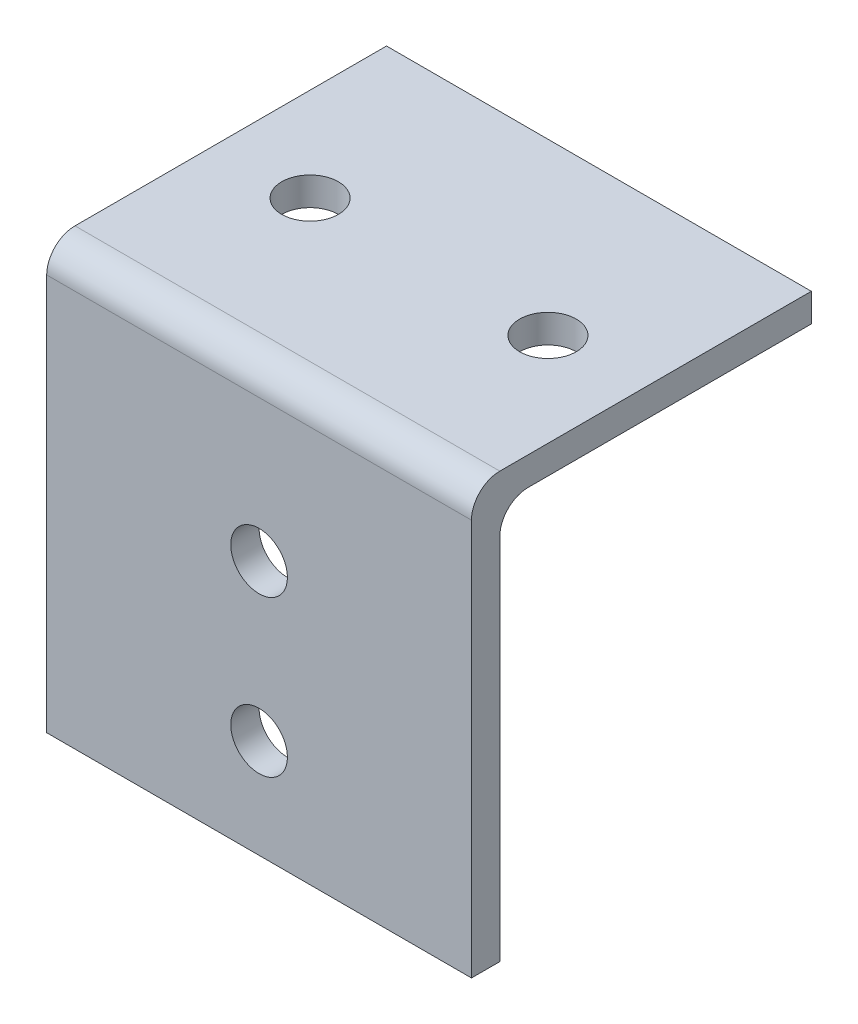
SolidWorks part; units mm, degrees
ref_plane "Front Plane" through (0, 0, 0) normal (0, 0, 1) x (1, 0, 0)
ref_plane "Top Plane" through (0, 0, 0) normal (0, 1, 0) x (1, 0, 0)
ref_plane "Right Plane" through (0, 0, 0) normal (1, 0, 0) x (0, 0, -1)
sketch "Sketch1" plane through (0, 0, 0) normal (0, 1, 0) x (1, 0, 0)
  line L0 (-19.5834, -8.6292) -> (18.5166, -8.6292) construction
  line L1 (-19.5834, 14.2308) -> (-5.08, 14.2308)
  line L2 (-19.5834, 14.2308) -> (-19.5834, -13.7092)
  line L3 (-19.5834, -13.7092) -> (18.5166, -13.7092)
  line L4 (18.5166, 14.2308) -> (18.5166, -13.7092)
  line L5 (-19.5834, -1.0092) -> (18.5166, -1.0092) construction
  line L6 (-5.08, 14.2308) -> (5.08, 14.2308)
  line L12 (5.08, 14.2308) -> (18.5166, 14.2308)
  circle A1 centre (-11.2014, -1.0092) radius 2.54
  circle A2 centre (10.1346, -1.0092) radius 2.54
  dimension "D1" = 22.86
  dimension "D4" = 5.08
  dimension "D5" = 5.08
  dimension "D2" = 38.1
  dimension "D3" = 27.94
  dimension "D6" = 8.382
  dimension "D7" = 8.382
  dimension "D9" = 15.24
extrude "Boss-Extrude1" add sketch "Sketch1" along normal blind 2.54
sketch "Sketch2" plane through (0, 0, 13.7092) normal (0, 0, 1) x (1, 0, 0)
  line L0 (18.5166, 2.54) -> (18.5166, 0) construction
  line L1 (-19.5834, 2.54) -> (18.5166, 2.54)
  line L2 (-19.5834, 2.54) -> (-19.5834, -35.56)
  line L3 (-19.5834, -35.56) -> (18.5166, -35.56)
  line L4 (18.5166, 2.54) -> (18.5166, -35.56)
  line L5 (-0.5334, 2.54) -> (-0.5334, -35.56) construction
  circle A0 centre (-0.5334, -12.7) radius 2.54
  circle A1 centre (-0.5334, -26.67) radius 2.54
  dimension "D2" = 5.08
  dimension "D3" = 5.08
  dimension "D1" = 38.1
  dimension "D4" = 13.97
  dimension "D5" = 15.24
extrude "Boss-Extrude2" add sketch "Sketch2" along normal blind 2.54
fillet "Fillet2" radius 2.54 1 edges at (-0.5334, 0, 13.7092)
fillet "Fillet3" radius 2.54 1 edges at (-0.5334, 2.54, 16.2492)
